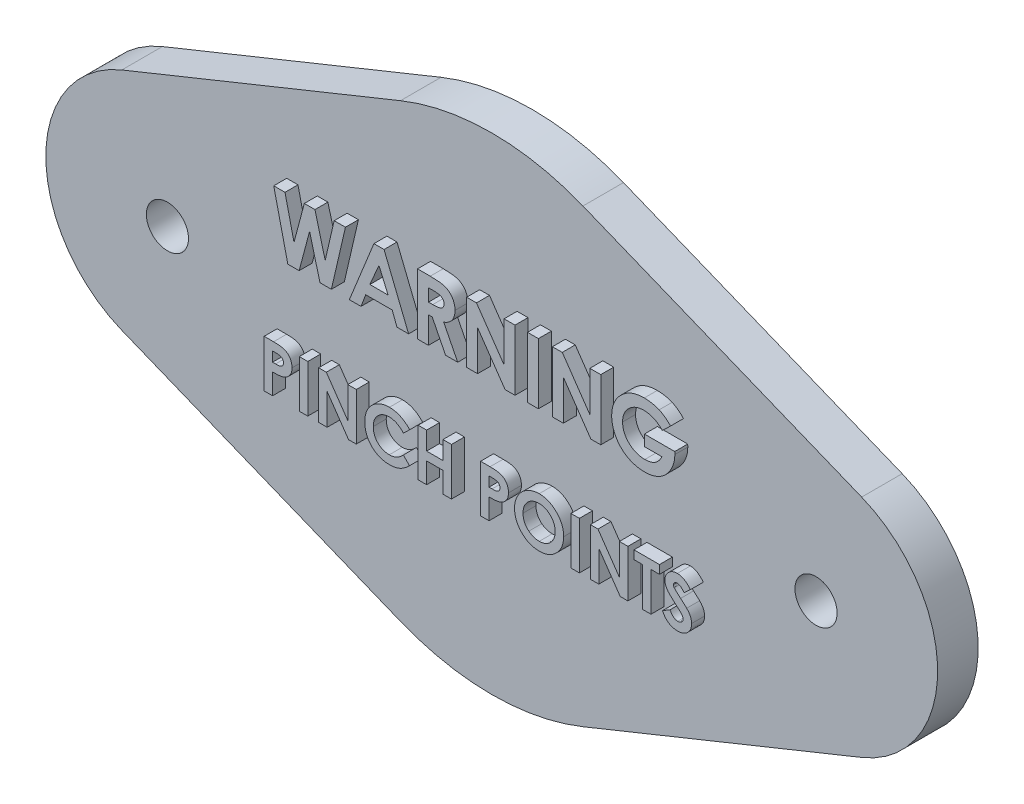
SolidWorks part; units mm, degrees
ref_plane "Front Plane" through (0, 0, 0) normal (0, 0, 1) x (1, 0, 0)
ref_plane "Top Plane" through (0, 0, 0) normal (0, 1, 0) x (1, 0, 0)
ref_plane "Right Plane" through (0, 0, 0) normal (1, 0, 0) x (0, 0, -1)
sketch "Sketch1" plane through (0, 0, 0) normal (0, 0, 1) x (1, 0, 0)
  line L0 (-69.85, 0) -> (69.85, 0) construction
  line L1 (0, -38.1) -> (0, 38.1) construction
  line L2 (-57.9437, 17.6598) -> (-14.2875, 35.3196)
  line L3 (14.2875, 35.3196) -> (57.9437, 17.6598)
  line L4 (14.2875, -35.3196) -> (57.9437, -17.6598)
  line L5 (-57.9437, -17.6598) -> (-14.2875, -35.3196)
  circle A0 centre (-50.8, 0) radius 19.05
  circle A1 centre (50.8, 0) radius 19.05
  circle A2 centre (0, 0) radius 38.1
  point P4 (0, 0)
  point P8 (0, 0)
  dimension "D3" = 38.1
  dimension "D4" = 76.2
  dimension "D1" = 139.7
  dimension "D2" = 76.2
extrude "Boss-Extrude1" add sketch "Sketch1" along normal blind 6.35 contours A2 A0 | A0 A2 | A2 L2 A0 | A1 A2 A0 | A2 A0 L5 | A2 L4 A1 | A1 A2 | A2 A1 | A2 A1 L3
sketch "Sketch2" plane through (0, 0, 6.35) normal (0, 0, 1) x (1, 0, 0)
  circle A0 centre (-50.8, 0) radius 3.302
  circle A1 centre (50.8, 0) radius 3.302
  dimension "D1" = 6.604
  dimension "D2" = 6.604
extrude "Cut-Extrude1" cut sketch "Sketch2" against normal through all
sketch "Sketch3" plane through (0, 0, 6.35) normal (0, 0, 1) x (1, 0, 0)
  line L0 (-35.6938, 6.35) -> (35.6938, 6.35) construction
  line L1 (0, 0) -> (27.0929, 0) construction
  line L2 (-35.6938, -12.7) -> (35.6938, -12.7) construction
  text T0 "<b>WARNING</b>" font "Century Gothic" height in points 36
  text T1 "<b>PINCH POINTS</b>" font "Century Gothic" height in points 28
  point P2 (0, 6.35)
  dimension "D1" = 6.35
  dimension "D2" = 12.7
extrude "Boss-Extrude2" add sketch "Sketch3" along normal blind 2.032 separate body
